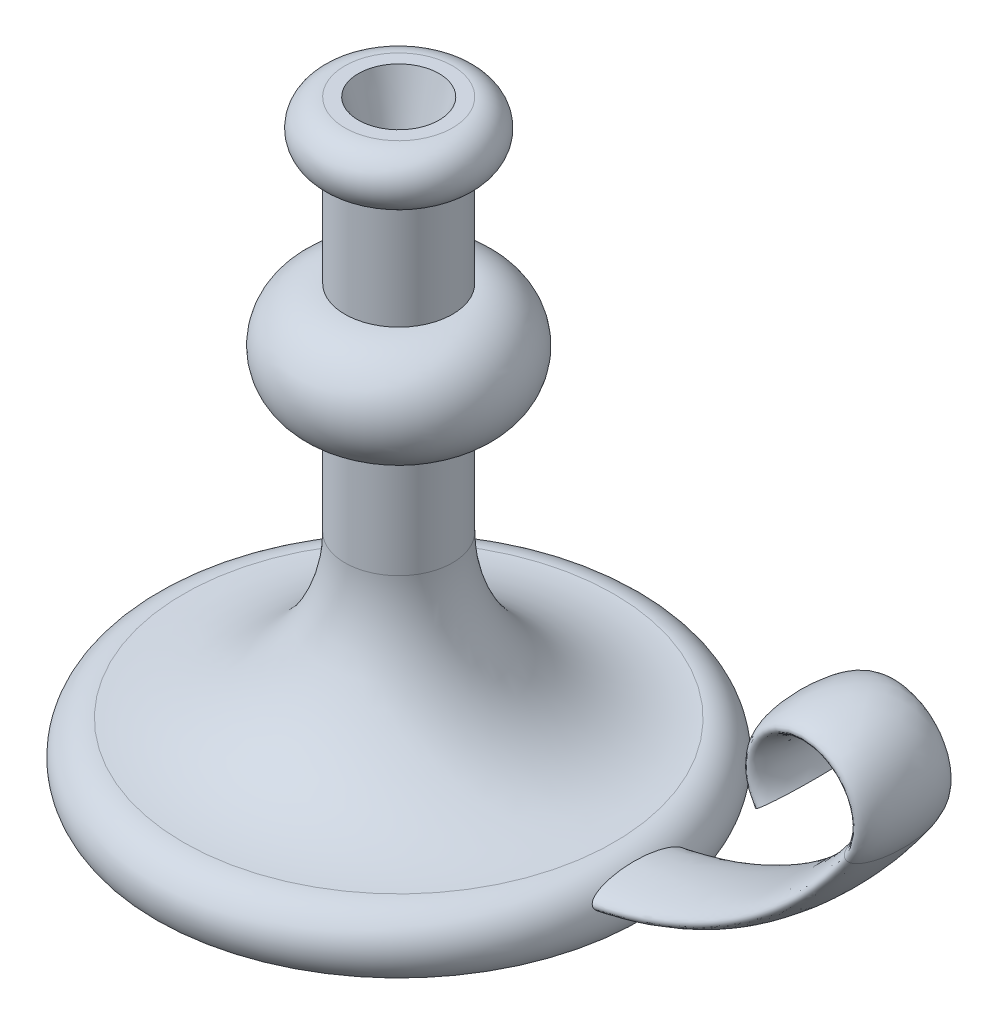
SolidWorks part; units mm, degrees
ref_plane "Front Plane" through (0, 0, 0) normal (0, 0, 1) x (1, 0, 0)
ref_plane "Top Plane" through (0, 0, 0) normal (0, 1, 0) x (1, 0, 0)
ref_plane "Right Plane" through (0, 0, 0) normal (1, 0, 0) x (0, 0, -1)
sketch "Sketch1" plane through (0, 0, 0) normal (0, 0, 1) x (1, 0, 0)
  line L0 (0, 0) -> (0, 220)
  line L1 (0, 220) -> (20, 220)
  line L2 (0, 0) -> (90, 0)
  line L3 (20, 200) -> (20, 160)
  line L4 (20, 120) -> (20, 80)
  arc A0 (20, 220) -> (20, 200) centre (20, 210) cw
  arc A1 (20, 160) -> (20, 120) centre (20, 140) cw
  arc A2 (20, 80) -> (80, 20) centre (80, 80) ccw
  arc A3 (80, 20) -> (90, 0) centre (80, 7.5) cw
  dimension "D4" = 10
  dimension "D5" = 20
  dimension "D7" = 60
  dimension "D9" = 12.5
  dimension "D1" = 220
  dimension "D2" = 20
  dimension "D3" = 90
  dimension "D6" = 40
  dimension "D8" = 80
revolve "Revolve1" add sketch "Sketch1" angle 360 about L0
sketch "Sketch2" plane through (0, 0, 0) normal (0, 0, 1) x (1, 0, 0)
  line L0 (0, 10) -> (60, 10)
  line L1 (0, 126.8188) -> (0, -13.6376) construction
  line L2 (-90, 0) -> (90, 0) construction
  arc A0 (60, 10) -> (183.5921, 75) centre (60, 160) ccw
  arc A1 (183.5921, 75) -> (150.6342, 75) centre (167.1131, 86.3333) ccw
  dimension "D2" = 150
  dimension "D4" = 20
  dimension "D1" = 60
  dimension "D3" = 65
  dimension "D5" = 10
sketch "Sketch3" plane through (0, 0, 0) normal (1, 0, 0) x (0, 0, -1)
  ellipse E0 centre (0, 10) end of major axis (17.5, 10) minor radius 5
  dimension "D1" = 35
  dimension "D2" = 10
sweep "Sweep1" add profiles "Sketch3" path "Sketch2"
sketch "Sketch5" plane through (0, 220, 0) normal (0, 1, 0) x (1, 0, 0)
  circle A0 centre (0, 0) radius 15
  dimension "D1" = 30
extrude "Cut-Extrude1" cut sketch "Sketch5" against normal blind 25 draft 15
